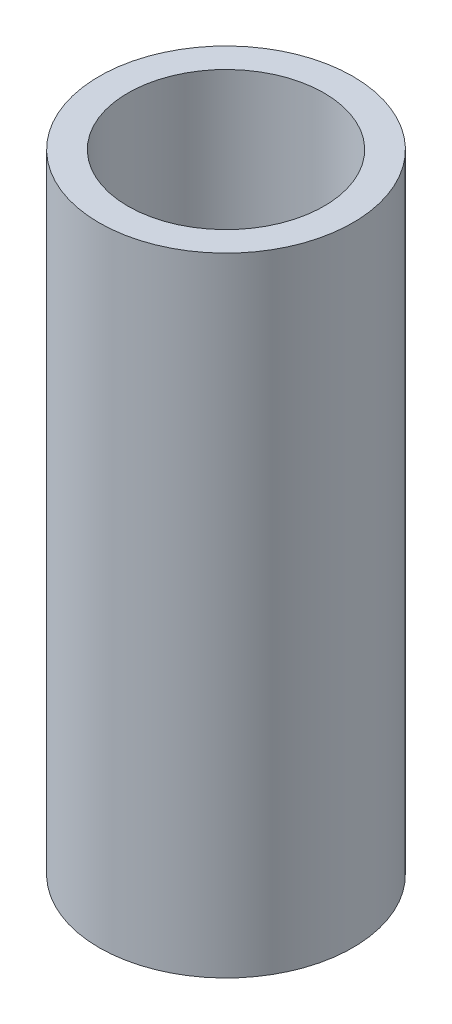
SolidWorks part; units mm, degrees
ref_plane "Front Plane" through (0, 0, 0) normal (0, 0, 1) x (1, 0, 0)
ref_plane "Top Plane" through (0, 0, 0) normal (0, 1, 0) x (1, 0, 0)
ref_plane "Right Plane" through (0, 0, 0) normal (1, 0, 0) x (0, 0, -1)
sketch "Sketch2" plane through (0, 0, 0) normal (0, 1, 0) x (1, 0, 0)
  circle A0 centre (0, 0) radius 1.5875
  circle A1 centre (0, 0) radius 2.0534
  dimension "D1" = 3.175
extrude "Boss-Extrude1" add sketch "Sketch2" along normal blind 10.16
